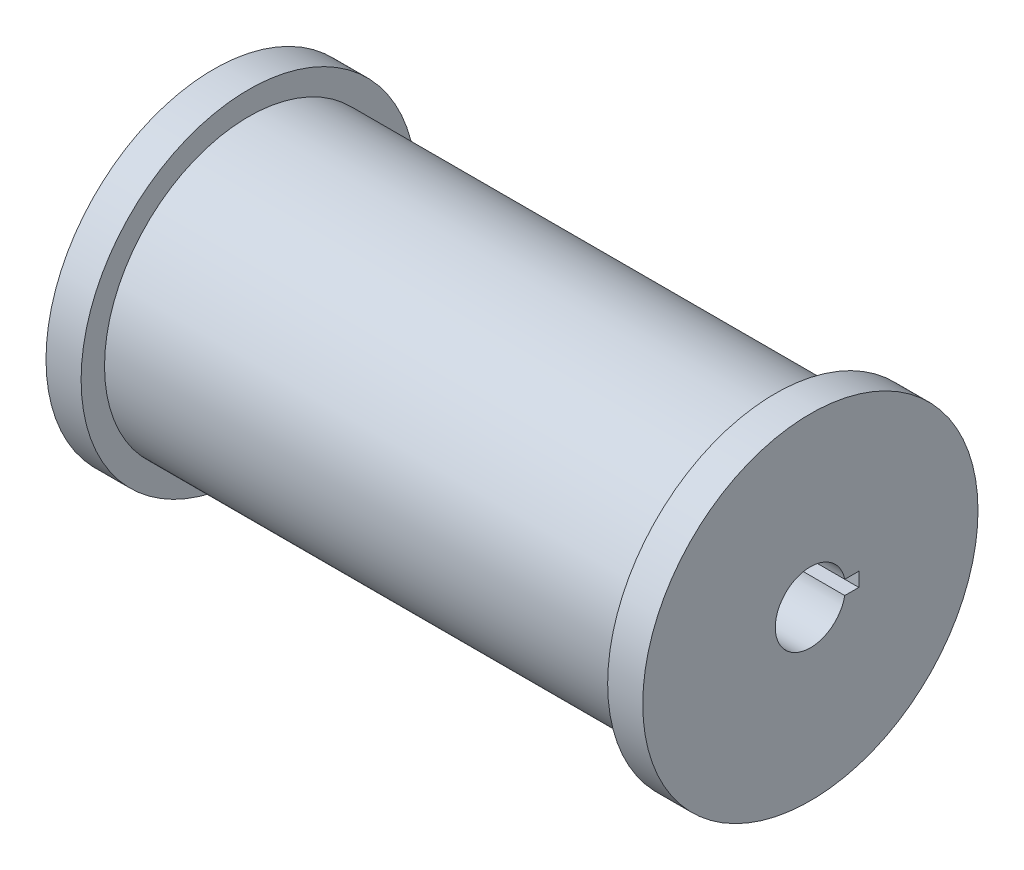
SolidWorks part; units mm, degrees
ref_plane "前视基准面" through (0, 0, 0) normal (0, 0, 1) x (1, 0, 0)
ref_plane "上视基准面" through (0, 0, 0) normal (0, 1, 0) x (1, 0, 0)
ref_plane "右视基准面" through (0, 0, 0) normal (1, 0, 0) x (0, 0, -1)
sketch "草图1" plane through (0, 0, 0) normal (0, 1, 0) x (1, 0, 0)
  line L0 (-58.3273, 0) -> (70.5845, 0) construction
  line L1 (0, 43.4285) -> (0, -42.7945) construction
  line L2 (-85, 10) -> (-85, 47.75)
  line L3 (-85, 47.75) -> (-75, 47.75)
  line L4 (85, 10) -> (85, 47.75)
  line L5 (-75, 47.75) -> (-75, 41.079)
  line L6 (-75, 41.079) -> (75, 41.079)
  line L7 (75, 47.75) -> (75, 41.079)
  line L8 (75, 47.75) -> (85, 47.75)
  line L10 (-85, 10) -> (85, 10)
  point P10 (0, 47.75)
  point P14 (0, 41.079)
  dimension "D3" = 150
  dimension "D1" = 170
  dimension "D2" = 47.75
revolve "旋转1" add sketch "草图1" angle 360 about L0
sketch "草图2" plane through (85, 0, 0) normal (1, 0, 0) x (0, 0, -1)
  line L0 (-20.5551, 0) -> (27.2636, 0) construction
  line L1 (9.798, 2) -> (13.798, 2)
  line L2 (13.798, 2) -> (13.798, -2)
  line L3 (9.798, -2) -> (13.798, -2)
  circle A0 centre (0, 0) radius 10 construction
  arc A1 (9.798, -2) -> (9.798, 2) centre (0, 0) ccw
  point P10 (13.798, 0)
  dimension "D1" = 4
  dimension "D2" = 4
extrude "切除-拉伸1" cut sketch "草图2" against normal blind 15
